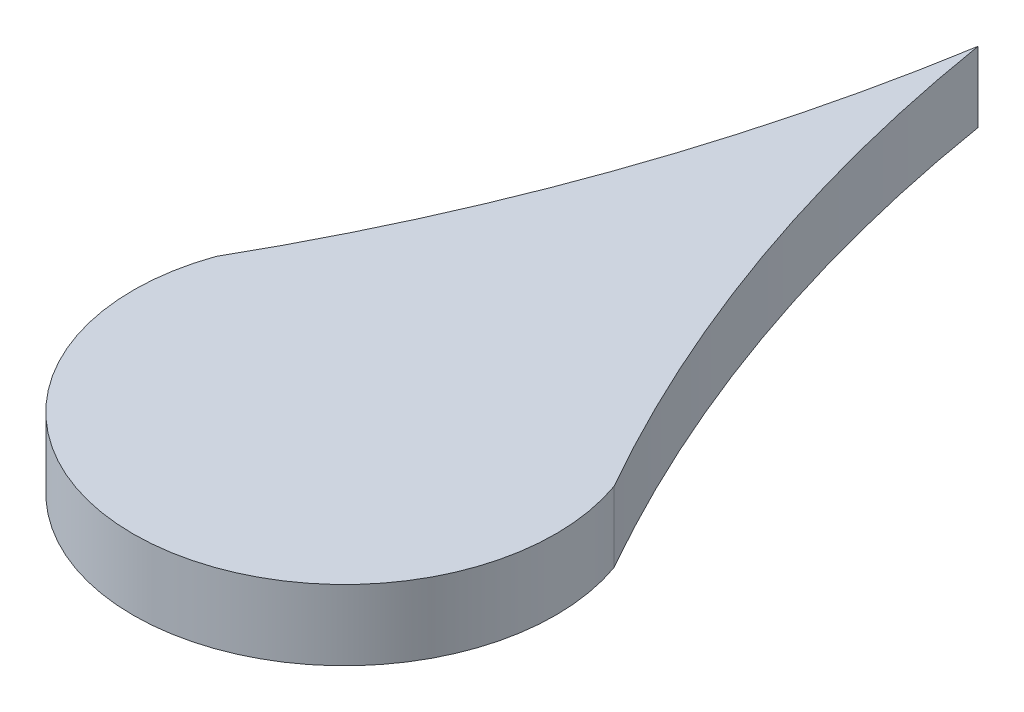
SolidWorks part; units mm, degrees
ref_plane "Front Plane" through (0, 0, 0) normal (0, 0, 1) x (1, 0, 0)
ref_plane "Top Plane" through (0, 0, 0) normal (0, 1, 0) x (1, 0, 0)
ref_plane "Right Plane" through (0, 0, 0) normal (1, 0, 0) x (0, 0, -1)
sketch "Sketch1" plane through (0, 0, 0) normal (0, 1, 0) x (1, 0, 0)
  line L0 (0, -3.7424) -> (0, 49996.2576) construction
  line L1 (-17.9605, 6.35) -> (17.9605, 6.35) construction
  arc A0 (-17.9605, 6.35) -> (17.9605, 6.35) centre (0, 0) ccw
  arc A1 (-17.9605, 6.35) -> (0, 57.15) centre (-150.4015, 81.7499) ccw
  arc A2 (17.9605, 6.35) -> (0, 57.15) centre (150.4015, 81.7499) cw
  point P4 (0, 57.15)
  point P8 (0, 57.15)
  point P11 (0, 0)
  point P13 (12.1862, -14.6423)
  point P14 (-19.05, 0)
  dimension "D1" = 152.4
  dimension "D3" = 19.05
  dimension "D2" = 6.35
  dimension "D4" = 57.15
extrude "Boss-Extrude1" add sketch "Sketch1" along normal blind 6.35
